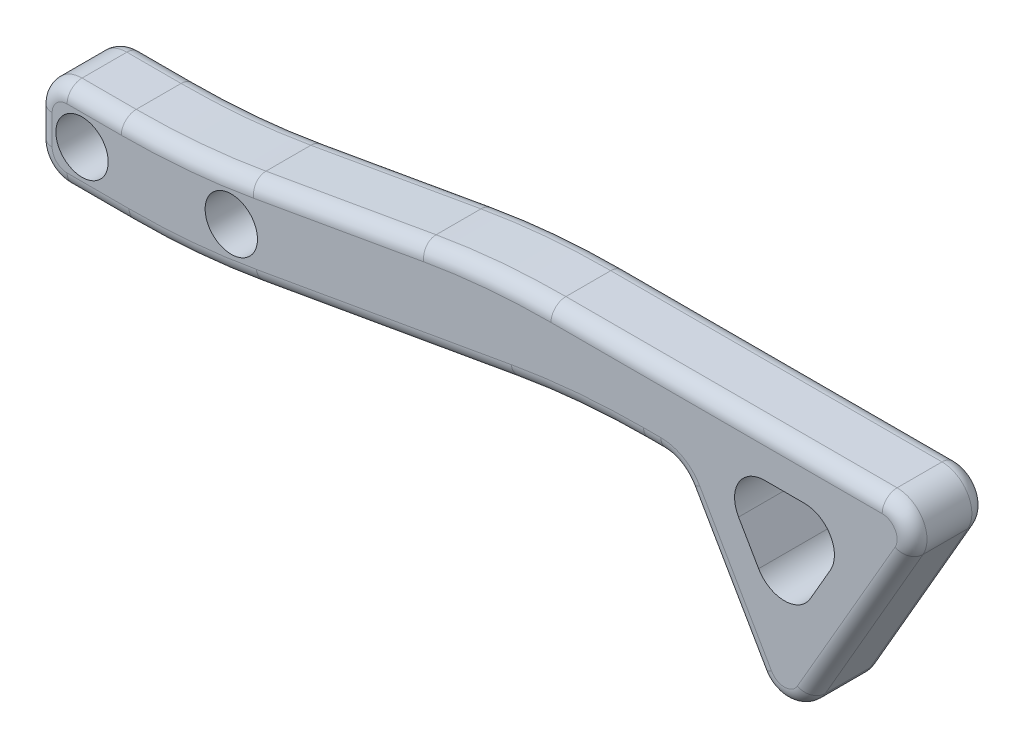
SolidWorks part; units mm, degrees
ref_plane "Front Plane" through (0, 0, 0) normal (0, 0, 1) x (1, 0, 0)
ref_plane "Top Plane" through (0, 0, 0) normal (0, 1, 0) x (1, 0, 0)
ref_plane "Right Plane" through (0, 0, 0) normal (1, 0, 0) x (0, 0, -1)
sketch "Sketch1" plane through (0, 0, 0) normal (0, 0, 1) x (1, 0, 0)
  line L0 (4.3744, 0) -> (26.5359, 0)
  line L1 (28.2679, -3) -> (21.7321, -14.3205)
  line L2 (18.2679, -14.3205) -> (13.4641, -6)
  line L3 (11.7321, -5) -> (10.5706, -5)
  line L4 (1.8882, -5.7596) -> (-15.1671, -8.7669)
  line L5 (-23.8495, -9.5265) -> (-28, -9.5265)
  line L6 (-30, -7.5265) -> (-30, -5.5265)
  line L7 (-28, -3.5265) -> (-24.3744, -3.5265)
  line L8 (-15.692, -2.7669) -> (-4.308, -0.7596)
  line L9 (21.7321, -8.3205) -> (23.0718, -6)
  line L10 (21.3397, -3) -> (18.6603, -3)
  line L11 (16.9282, -6) -> (18.2679, -8.3205)
  arc A0 (-28, -9.5265) -> (-30, -7.5265) centre (-28, -7.5265) cw
  arc A1 (-30, -5.5265) -> (-28, -3.5265) centre (-28, -5.5265) cw
  arc A2 (13.4641, -6) -> (11.7321, -5) centre (11.7321, -7) ccw
  arc A3 (18.6603, -3) -> (16.9282, -6) centre (18.6603, -5) ccw
  arc A4 (23.0718, -6) -> (21.3397, -3) centre (21.3397, -5) ccw
  arc A5 (26.5359, 0) -> (28.2679, -3) centre (26.5359, -2) cw
  arc A6 (21.7321, -8.3205) -> (18.2679, -8.3205) centre (20, -7.3205) cw
  arc A7 (21.7321, -14.3205) -> (18.2679, -14.3205) centre (20, -13.3205) cw
  arc A8 (10.5706, -5) -> (1.8882, -5.7596) centre (10.5706, -55) ccw
  arc A9 (4.3744, 0) -> (-4.308, -0.7596) centre (4.3744, -50) ccw
  arc A10 (-15.1671, -8.7669) -> (-23.8495, -9.5265) centre (-23.8495, 40.4735) cw
  arc A11 (-24.3744, -3.5265) -> (-15.692, -2.7669) centre (-24.3744, 46.4735) ccw
  point P13 (-30, -9.5265)
  point P18 (-30, -3.5265)
  point P27 (30, 0)
  point P32 (20, -17.3205)
  point P37 (0, 0)
  point P42 (-20, -3.5265)
  dimension "D14" = 2
  dimension "D15" = 50
  dimension "D1" = 30
  dimension "D2" = 10
  dimension "D3" = 20
  dimension "D4" = 10
  dimension "D5" = 6
  dimension "D6" = 6
  dimension "D7" = 5
  dimension "D8" = 60
  dimension "D9" = 60
  dimension "D10" = 20
  dimension "D11" = 3
  dimension "D12" = 3
  dimension "D13" = 3
extrude "Boss-Extrude1" add sketch "Sketch1" along normal blind 5
fillet "Fillet1" radius 1 36 edges at (0.0166, -0.1903, 0) (15.4552, 0, 0) (28.2679, -1, 0) (25, -8.6603, 0) (20, -15.3205, 0) (15.866, -10.1603, 0) (12.7321, -5.2679, 0) (11.1513, -5, 0) (6.2129, -5.1903, 0) (-6.6394, -7.2633, 0) (-19.4917, -9.3363, 0) (-25.9248, -9.5265, 0) (-29.4142, -8.9408, 0) (-30, -6.5265, 0) (-29.4142, -4.1123, 0) (-26.1872, -3.5265, 0) (-20.0166, -3.3363, 0) (-10, -1.7633, 5) (0.0166, -0.1903, 5) (15.4552, 0, 5) (28.2679, -1, 5) (25, -8.6603, 5) (20, -15.3205, 5) (15.866, -10.1603, 5) (12.7321, -5.2679, 5) (11.1513, -5, 5) (6.2129, -5.1903, 5) (-6.6394, -7.2633, 5) (-19.4917, -9.3363, 5) (-25.9248, -9.5265, 5) (-29.4142, -8.9408, 5) (-30, -6.5265, 5) (-29.4142, -4.1123, 5) (-26.1872, -3.5265, 5) (-10, -1.7633, 0) (-20.0166, -3.3363, 5)
sketch "Sketch2" plane through (0, 0, 5) normal (0, 0, 1) x (1, 0, 0)
  line L0 (-27, -6.5265) -> (-17.0139, -5.9996) construction
  line L1 (-27, -6.5265) -> (-30, -6.5265) construction
  line L2 (-30, -7.5265) -> (-30, -5.5265) construction
  circle A0 centre (-17.0139, -5.9996) radius 1.75
  circle A1 centre (-27, -6.5265) radius 1.75
  point P4 (-17.0139, -5.9996)
  dimension "D2" = 3.5
  dimension "D1" = 10
  dimension "D3" = 3
extrude "Cut-Extrude1" cut sketch "Sketch2" against normal through all
